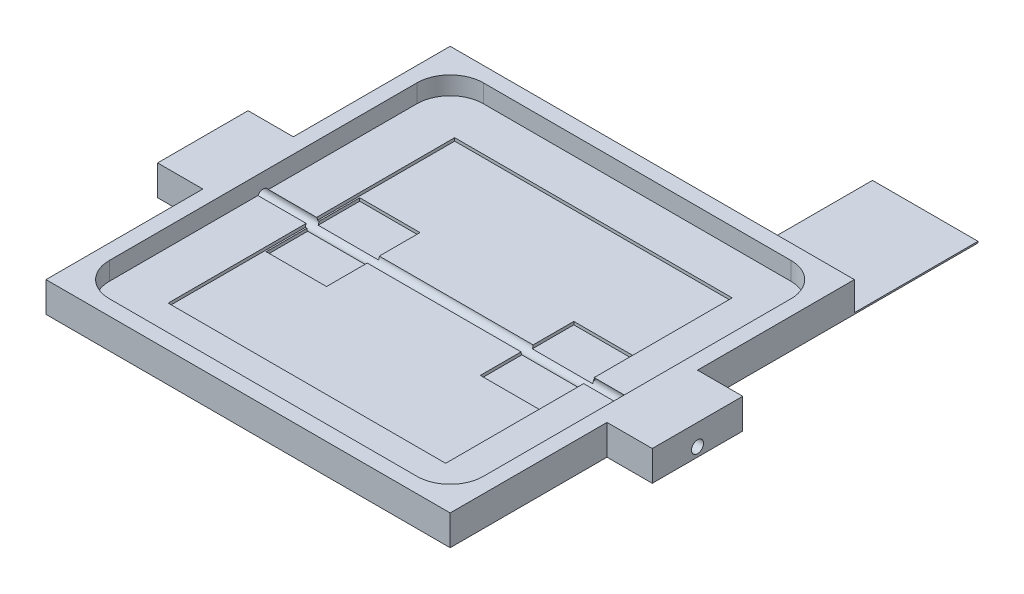
SolidWorks part; units mm, degrees
ref_plane "Front Plane" through (0, 0, 0) normal (0, 0, 1) x (1, 0, 0)
ref_plane "Top Plane" through (0, 0, 0) normal (0, 1, 0) x (1, 0, 0)
ref_plane "Right Plane" through (0, 0, 0) normal (1, 0, 0) x (0, 0, -1)
sketch "Sketch1" plane through (0, 0, 0) normal (0, 1, 0) x (1, 0, 0)
  line L0 (-67, -15) -> (-67, -67)
  line L1 (-67, 67) -> (67, 67)
  line L2 (-67, 67) -> (-67, 15)
  line L3 (-67, -67) -> (67, -67)
  line L4 (67, 67) -> (67, 15)
  line L5 (67, -15) -> (82, -15)
  line L6 (67, 15) -> (82, 15)
  line L7 (-82, 15) -> (-67, 15)
  line L8 (-82, 15) -> (-82, -15)
  line L9 (-82, -15) -> (-67, -15)
  line L10 (82, 15) -> (82, -15)
  line L13 (67, -15) -> (67, -67)
  point P0 (0, 0)
  point P6 (0, 0)
  dimension "D1" = 134
  dimension "D2" = 134
  dimension "D3" = 164
  dimension "D4" = 30
extrude "Boss-Extrude1" add sketch "Sketch1" along normal blind 10
sketch "Sketch2" plane through (0, 10, 0) normal (0, 1, 0) x (1, 0, 0)
  line L1 (-62, 62) -> (62, 62)
  line L2 (-62, 62) -> (-62, -62)
  line L3 (-62, -62) -> (62, -62)
  line L4 (62, 62) -> (62, -62)
  line L5 (-62, 62) -> (62, -62) construction
  line L6 (-62, -62) -> (62, 62) construction
  point P0 (0, 0)
  dimension "D1" = 124
  dimension "D2" = 124
sketch "Sketch9" plane through (82, 0, 0) normal (1, 0, 0) x (0, 0, -1)
  line L0 (0, 0) -> (0, 3) construction
  circle A0 centre (0, 3) radius 2
  dimension "D2" = 4
  dimension "D1" = 3
extrude "Cut-Extrude14" cut sketch "Sketch9" against normal blind 181
extrude "Cut-Extrude15" cut sketch "Sketch2" against normal blind 6
sketch "Sketch10" plane through (0, 4, 0) normal (0, 1, 0) x (1, 0, 0)
  line L0 (62, -62) -> (62, 62) construction
  line L1 (25.5, 15.5) -> (45.5, 15.5)
  line L2 (25.5, 15.5) -> (25.5, -15.5)
  line L3 (25.5, -15.5) -> (45.5, -15.5)
  line L4 (45.5, 15.5) -> (45.5, -15.5)
  line L5 (0, 0) -> (87.3792, 0) construction
  line L6 (0, 36.0297) -> (0, -30.1666) construction
  line L7 (-25.5, -15.5) -> (-45.5, -15.5)
  line L8 (-45.5, 15.5) -> (-45.5, -15.5)
  line L9 (-25.5, 15.5) -> (-45.5, 15.5)
  line L10 (-25.5, 15.5) -> (-25.5, -15.5)
  dimension "D1" = 16.5
  dimension "D2" = 31
  dimension "D3" = 20
  dimension "D4" = 15.5
extrude "Cut-Extrude17" cut sketch "Sketch10" against normal blind 2
sketch "Sketch11" plane through (0, 4, 0) normal (0, 1, 0) x (1, 0, 0)
  line L1 (-46, 47.5) -> (46, 47.5)
  line L2 (-46, 47.5) -> (-46, -47.5)
  line L3 (-46, -47.5) -> (46, -47.5)
  line L4 (46, 47.5) -> (46, -47.5)
  line L5 (-46, 47.5) -> (46, -47.5) construction
  line L6 (-46, -47.5) -> (46, 47.5) construction
  point P0 (0, 0)
  dimension "D1" = 92
  dimension "D2" = 95
extrude "Cut-Extrude18" cut sketch "Sketch11" against normal blind 1
sketch "Sketch12" plane through (0, 3, 0) normal (0, 1, 0) x (1, 0, 0)
fillet "Fillet3" radius 11 4 edges at (62, 7, -62) (62, 7, 62) (-62, 7, 62) (-62, 7, -62)
sketch "Sketch13" plane through (0, 0, -67) normal (0, 0, -1) x (-1, 0, 0)
  line L1 (-67, 0) -> (-32.0173, 0)
  line L2 (-67, 0) -> (-67, 0.5)
  line L3 (-67, 0.5) -> (-32.0173, 0.5)
  line L4 (-32.0173, 0) -> (-32.0173, 0.5)
  point P7 (-166.4751, -0.8272)
  dimension "D1" = 0.5
extrude "Boss-Extrude3" add sketch "Sketch13" along normal blind 41
